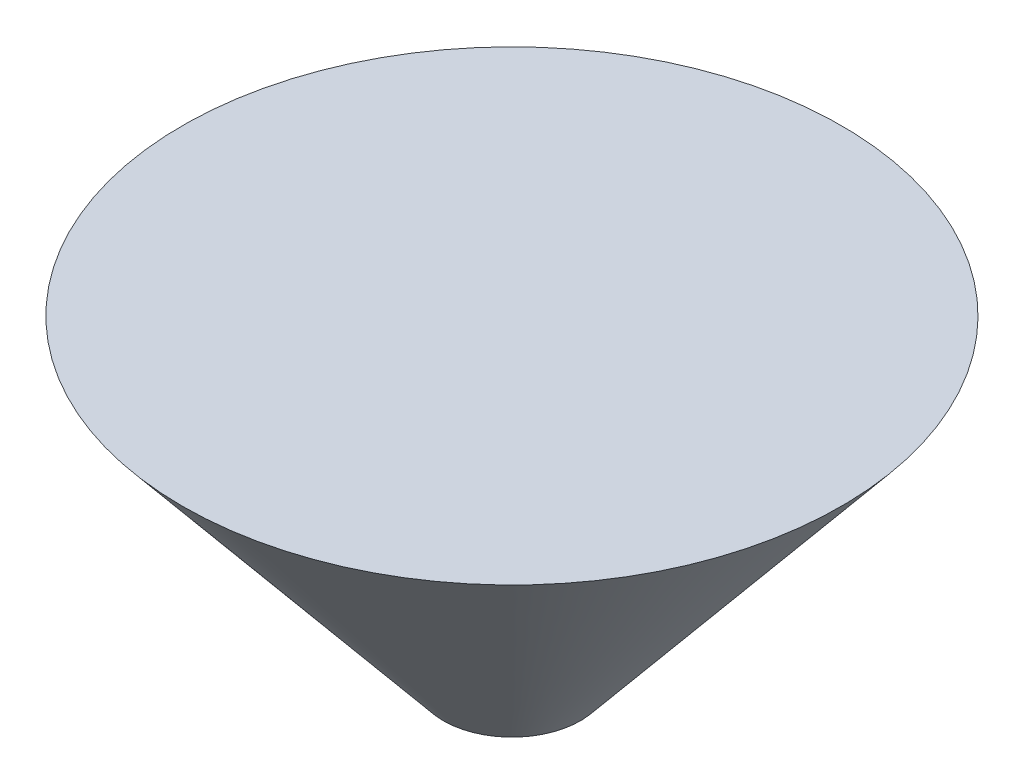
SolidWorks part; units mm, degrees
material "Nylon 101"
ref_plane "Alzado" through (0, 0, 0) normal (0, 0, 1) x (1, 0, 0)
ref_plane "Planta" through (0, 0, 0) normal (0, 1, 0) x (1, 0, 0)
ref_plane "Vista lateral" through (0, 0, 0) normal (1, 0, 0) x (0, 0, -1)
sketch "Sketch1" plane through (0, 0, 0) normal (0, 0, 1) x (1, 0, 0)
  line L0 (0, 0) -> (12.5, 0)
  line L1 (12.5, 0) -> (2.6, -12)
  line L2 (2.6, -12) -> (0, -12)
  line L3 (0, -12) -> (0, 0)
  line L4 (0, -16) -> (0, 4) construction
revolve "Cono_de_union" add sketch "Sketch1" angle 360 about L4
